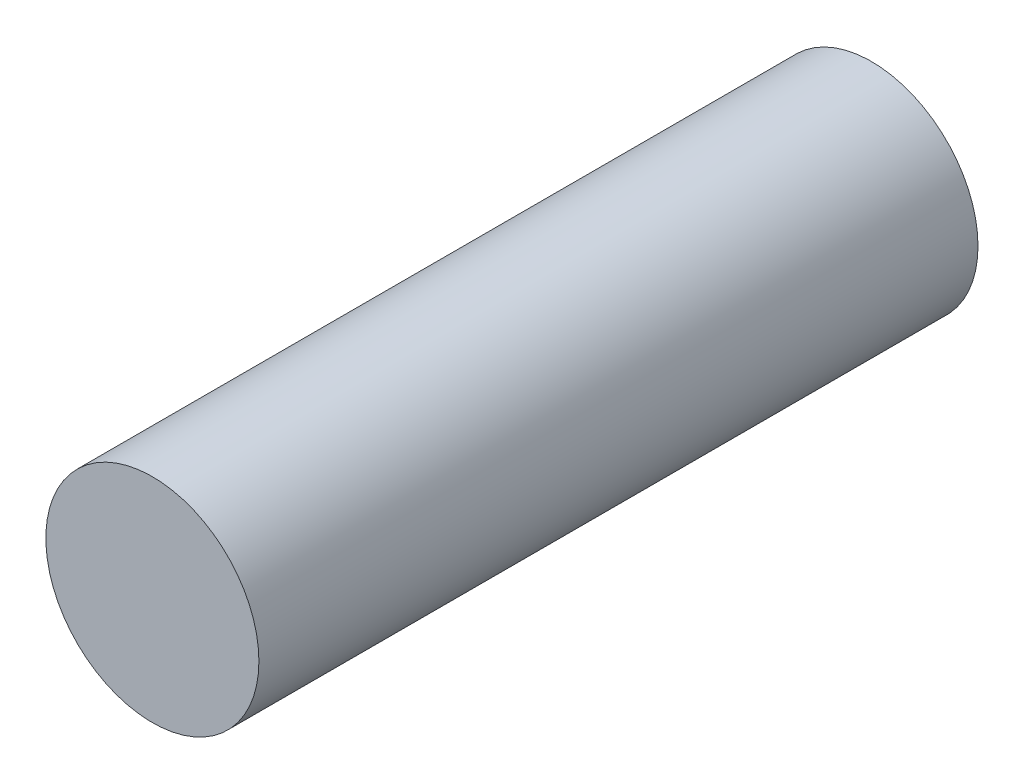
SolidWorks part; units mm, degrees
ref_plane "Front Plane" through (0, 0, 0) normal (0, 0, 1) x (1, 0, 0)
ref_plane "Top Plane" through (0, 0, 0) normal (0, 1, 0) x (1, 0, 0)
ref_plane "Right Plane" through (0, 0, 0) normal (1, 0, 0) x (0, 0, -1)
sketch "Sketch1" plane through (0, 0, 0) normal (0, 0, 1) x (1, 0, 0)
  circle A0 centre (0, 0) radius 4
  dimension "D1" = 8
extrude "Boss-Extrude1" add sketch "Sketch1" along normal blind 27
